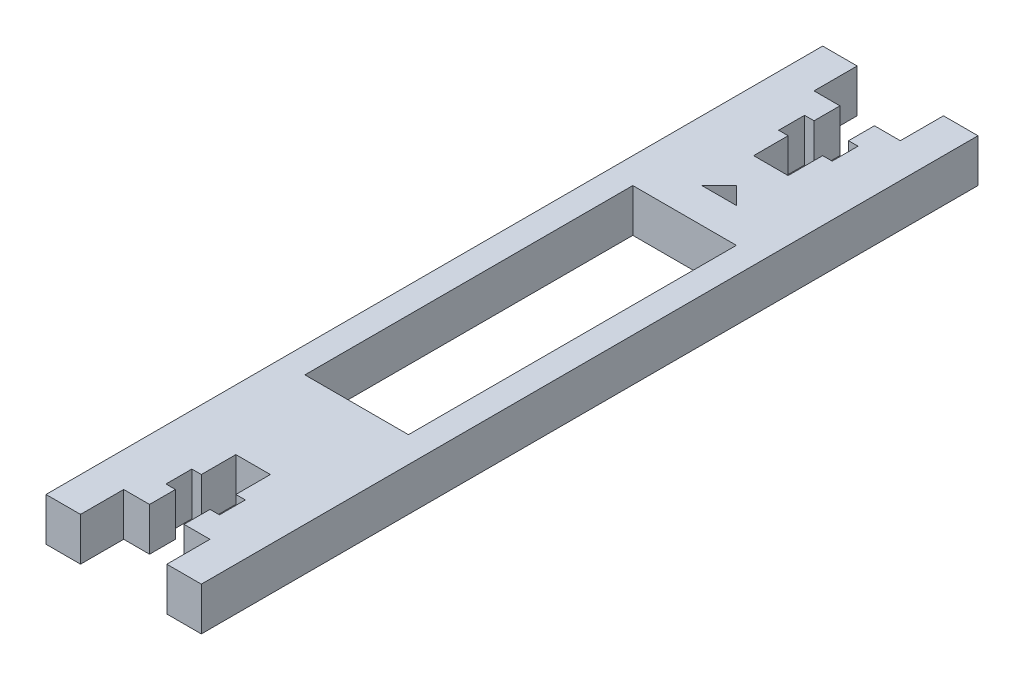
SolidWorks part; units mm, degrees
ref_plane "Front Plane" through (0, 0, 0) normal (0, 0, 1) x (1, 0, 0)
ref_plane "Top Plane" through (0, 0, 0) normal (0, 1, 0) x (1, 0, 0)
ref_plane "Right Plane" through (0, 0, 0) normal (1, 0, 0) x (0, 0, -1)
sketch "Sketch1" plane through (0, 0, 0) normal (0, 1, 0) x (1, 0, 0)
  line L0 (-3.6453, 61.367) -> (-3.6453, -18.633) construction
  line L1 (-8.6453, 61.367) -> (-5.6453, 61.367)
  line L2 (-12.6453, 61.367) -> (-12.6453, 16.367)
  line L3 (-8.6453, -18.633) -> (-5.6453, -18.633)
  line L4 (5.3547, 61.367) -> (5.3547, 16.367)
  line L5 (-12.6453, -23.633) -> (-8.6453, -23.633)
  line L7 (5.3547, -18.633) -> (5.3547, -23.633)
  line L8 (5.3547, -23.633) -> (1.3547, -23.633)
  line L9 (1.3547, -18.633) -> (1.3547, -23.633)
  line L10 (-8.6453, -18.633) -> (-8.6453, -23.633)
  line L11 (-12.6453, -18.633) -> (-12.6453, -23.633)
  line L21 (5.3547, -3.633) -> (5.3547, -18.633)
  line L22 (-12.6453, 16.367) -> (-12.6453, -3.633)
  line L37 (5.3547, -3.633) -> (5.3547, 16.367)
  line L38 (-22.4352, 41.367) -> (17.4937, 41.367) construction
  line L39 (2.3547, 41.367) -> (2.3547, 3.367)
  line L40 (-9.6453, 41.367) -> (2.3547, 41.367)
  line L41 (-9.6453, 41.367) -> (-9.6453, 3.367)
  line L42 (-9.6453, 3.367) -> (2.3547, 3.367)
  line L44 (-5.6453, 45.367) -> (-1.6453, 45.367)
  line L45 (-1.6453, 45.367) -> (-3.6453, 47.367)
  line L48 (5.3547, 16.367) -> (5.3547, 31.367)
  line L49 (-5.6453, 45.367) -> (-3.6453, 47.367)
  line L56 (5.3547, -48.633) -> (5.3547, -3.633)
  line L58 (-12.6453, -48.633) -> (-12.6453, -3.633)
  line L66 (-12.6453, 16.367) -> (-12.6453, 31.367)
  line L90 (-12.6453, -3.633) -> (-12.6453, -18.633)
  line L98 (-12.6453, 61.367) -> (-12.6453, 16.367)
  line L101 (-12.6453, -3.633) -> (-12.6453, -18.633)
  line L102 (-1.6453, -18.633) -> (1.3547, -18.633)
  line L106 (-5.6453, -18.633) -> (-5.6453, -15.633)
  line L107 (-5.6453, -12.633) -> (-6.7453, -12.633)
  line L109 (-5.6453, -15.633) -> (-6.7453, -15.633)
  line L110 (-6.7453, -12.633) -> (-6.7453, -15.633)
  line L111 (-5.6453, -12.633) -> (-5.6453, -8.633)
  line L112 (-1.6453, -15.633) -> (-0.5453, -15.633)
  line L113 (-5.6453, -8.633) -> (-1.6453, -8.633)
  line L114 (-5.6453, -8.633) -> (-5.6453, -12.633)
  line L117 (-1.6453, -12.633) -> (-0.5453, -12.633)
  line L118 (-0.5453, -12.633) -> (-0.5453, -15.633)
  line L119 (-1.6453, -18.633) -> (-1.6453, -15.633)
  line L120 (-1.6453, -12.633) -> (-1.6453, -8.633)
  line L121 (-5.6453, -15.633) -> (-5.6453, -18.633)
  line L122 (-3.6453, 21.367) -> (23.4497, 21.367) construction
  line L123 (-5.6453, 58.367) -> (-5.6453, 61.367)
  line L124 (-1.6453, 55.367) -> (-1.6453, 51.367)
  line L125 (-1.6453, 61.367) -> (-1.6453, 58.367)
  line L126 (-0.5453, 55.367) -> (-0.5453, 58.367)
  line L127 (-1.6453, 55.367) -> (-0.5453, 55.367)
  line L128 (-5.6453, 51.367) -> (-5.6453, 55.367)
  line L129 (-5.6453, 51.367) -> (-1.6453, 51.367)
  line L130 (-1.6453, 58.367) -> (-0.5453, 58.367)
  line L131 (-5.6453, 55.367) -> (-5.6453, 51.367)
  line L132 (-6.7453, 55.367) -> (-6.7453, 58.367)
  line L133 (-5.6453, 58.367) -> (-6.7453, 58.367)
  line L134 (-5.6453, 55.367) -> (-6.7453, 55.367)
  line L135 (-5.6453, 61.367) -> (-5.6453, 58.367)
  line L136 (-1.6453, 61.367) -> (1.3547, 61.367)
  line L137 (-12.6453, 61.367) -> (-12.6453, 66.367)
  line L138 (-8.6453, 61.367) -> (-8.6453, 66.367)
  line L139 (1.3547, 61.367) -> (1.3547, 66.367)
  line L140 (5.3547, 66.367) -> (1.3547, 66.367)
  line L141 (5.3547, 61.367) -> (5.3547, 66.367)
  line L142 (-12.6453, 66.367) -> (-8.6453, 66.367)
  line L143 (-8.6453, 61.367) -> (-5.6453, 61.367)
  line L144 (-1.6453, 61.367) -> (1.3547, 61.367)
  point P24 (-3.6453, 45.367)
  dimension "D1" = 18
  dimension "D2" = 80
  dimension "D3" = 5
  dimension "D4" = 5
  dimension "D5" = 3
  dimension "D6" = 3
  dimension "D7" = 4
  dimension "D8" = 4
  dimension "D9" = 20
  dimension "D10" = 38
  dimension "D11" = 3
  dimension "D12" = 4
extrude "Boss-Extrude4" add sketch "Sketch1" along normal blind 5 contours L142 L137 L2 L22 L58 L11 L5 L10 L3 L106 L109 L110 L107 L111 L113 L120 L117 L118 L112 L119 L102 L9 L8 L7 L21 L37 L4 L141 L140 L139 L136 L125 L130 L126 L127 L124 L129 L128 L134 L132 L133 L123 L1 L138 L42 L41 L40 L39
